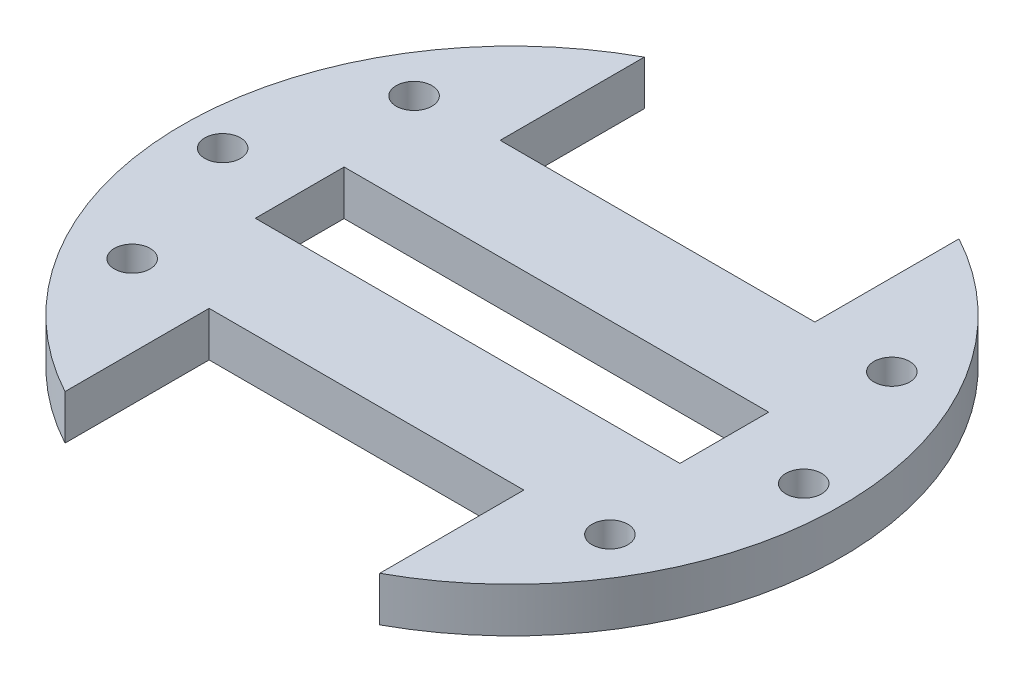
SolidWorks part; units mm, degrees
ref_plane "前视基准面" through (0, 0, 0) normal (0, 0, 1) x (1, 0, 0)
ref_plane "上视基准面" through (0, 0, 0) normal (0, 1, 0) x (1, 0, 0)
ref_plane "右视基准面" through (0, 0, 0) normal (1, 0, 0) x (0, 0, -1)
sketch "草图1" plane through (0, 0, 0) normal (0, 1, 0) x (1, 0, 0)
  circle A0 centre (0, 0) radius 29.5
  dimension "D1" = 59
extrude "凸台-拉伸1" add sketch "草图1" along normal blind 4 contours A0
sketch "草图2" plane through (0, 4, 0) normal (0, 1, 0) x (1, 0, 0)
  line L0 (-42.9641, 0) -> (48.0853, 0) construction
  line L1 (0, 36.4097) -> (0, -43.4956) construction
  line L6 (0, -45.977) -> (0, -13.023) construction
  line L7 (-14.0831, 13.023) -> (14.0831, 13.023)
  line L8 (-14.0831, 13.023) -> (-14.0831, 45.977)
  line L9 (-14.0831, 45.977) -> (14.0831, 45.977)
  line L10 (14.0831, 13.023) -> (14.0831, 45.977)
  line L11 (0, 45.977) -> (0, 13.023) construction
  line L12 (-14.0831, 29.5) -> (14.0831, 29.5) construction
  line L13 (14.0831, -29.5) -> (-14.0831, -29.5) construction
  line L14 (14.0831, -13.023) -> (14.0831, -45.977)
  line L15 (14.0831, -13.023) -> (-14.0831, -13.023)
  line L16 (-14.0831, -13.023) -> (-14.0831, -45.977)
  line L17 (14.0831, -45.977) -> (-14.0831, -45.977)
  circle A0 centre (0, 0) radius 29.5 construction
  point P4 (0, 29.5)
  point P17 (0, -29.5)
  point P26 (0, 0)
  dimension "D1" = 2
extrude "切除-拉伸1" cut sketch "草图2" against normal through all
sketch "草图3" plane through (0, 4, 0) normal (0, 1, 0) x (1, 0, 0)
  line L1 (-19, -3.9732) -> (19, -3.9732)
  line L2 (-19, -3.9732) -> (-19, 3.9732)
  line L3 (-19, 3.9732) -> (19, 3.9732)
  line L4 (19, -3.9732) -> (19, 3.9732)
  line L5 (0, 3.9732) -> (0, -3.9732) construction
  line L6 (-19, 0) -> (19, 0) construction
  point P0 (0, 0)
  dimension "D1" = 38
extrude "切除-拉伸2" cut sketch "草图3" against normal through all
sketch "草图6" plane through (0, 4, 0) normal (0, 1, 0) x (1, 0, 0)
  line L0 (-8.4052, 0) -> (-58.0435, 0) construction
  line L1 (0, 24.9966) -> (0, -33.499) construction
  circle A0 centre (-25.8936, 0) radius 1.6
  circle A1 centre (26.1064, 0) radius 1.6
  circle A10 centre (-21.376, 12.613) radius 1.6
  circle A11 centre (21.376, 12.613) radius 1.6
  circle A12 centre (-21.376, -12.613) radius 1.6
  circle A13 centre (21.376, -12.613) radius 1.6
  point P23 (0, 0)
  dimension "D1" = 3.2
  dimension "D2" = 3.2
  dimension "D4" = 42.752
  dimension "D5" = 25.226
  dimension "D3" = 52
extrude "切除-拉伸5" cut sketch "草图6" against normal through all
